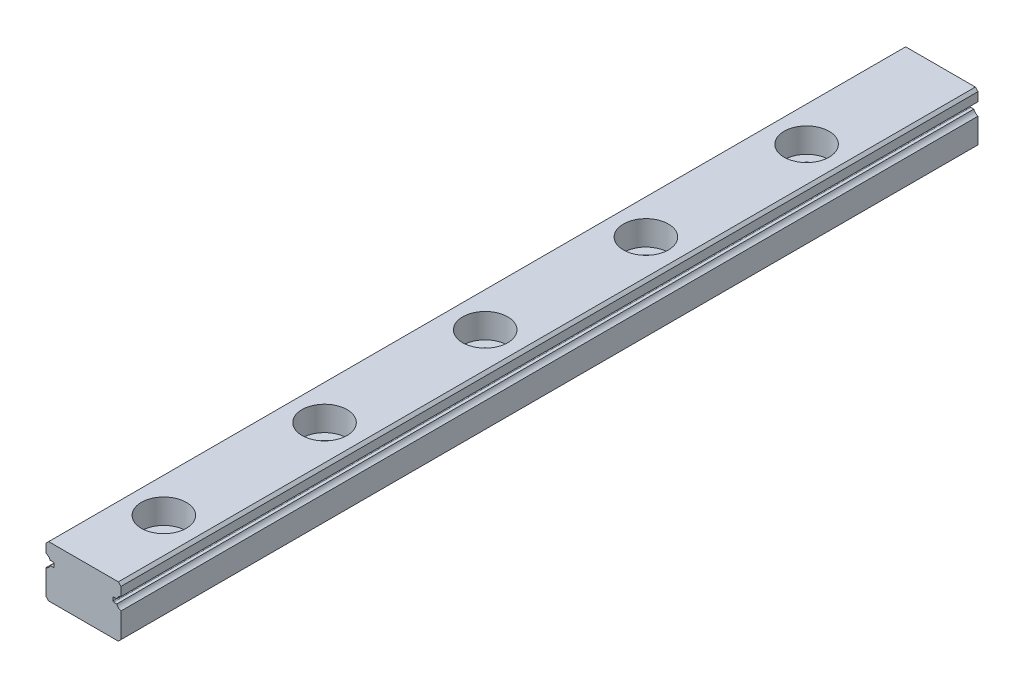
SolidWorks part; units mm, degrees
material "AISI 304"
ref_plane "前视基准面" through (0, 0, 0) normal (0, 0, 1) x (1, 0, 0)
ref_plane "上视基准面" through (0, 0, 0) normal (0, 1, 0) x (1, 0, 0)
ref_plane "右视基准面" through (0, 0, 0) normal (1, 0, 0) x (0, 0, -1)
other "Configuration Table"
sketch "草图2" plane through (0, 0, 0) normal (0, 0, 1) x (1, 0, 0)
  line L0 (3.2525, 4.8) -> (-3.2525, 4.8)
  line L1 (3.5, 4.5525) -> (3.2525, 4.8)
  line L2 (3.5, 3.7313) -> (3.5, 4.5525)
  line L3 (3.1055, 3.36) -> (2.8255, 3.36)
  line L4 (2.7555, 3.29) -> (2.7555, 3.01)
  line L5 (3.1055, 2.94) -> (2.8255, 2.94)
  line L6 (3.5, 0.2475) -> (3.5, 2.5687)
  line L7 (3.2525, 0) -> (3.5, 0.2475)
  line L8 (-3.2525, 0) -> (3.2525, 0)
  line L9 (-3.2525, 0) -> (-3.5, 0.2475)
  line L10 (-3.5, 0.2475) -> (-3.5, 2.5687)
  line L11 (-3.1055, 2.94) -> (-2.8255, 2.94)
  line L12 (-2.7555, 3.29) -> (-2.7555, 3.01)
  line L13 (-3.1055, 3.36) -> (-2.8255, 3.36)
  line L14 (-3.5, 3.7313) -> (-3.5, 4.5525)
  line L15 (-3.5, 4.5525) -> (-3.2525, 4.8)
  arc A0 (3.5, 3.7313) -> (3.1055, 3.36) centre (3.675, 3.15) ccw
  arc A1 (2.8255, 3.36) -> (2.7555, 3.29) centre (2.8255, 3.29) ccw
  arc A2 (2.7555, 3.01) -> (2.8255, 2.94) centre (2.8255, 3.01) ccw
  arc A3 (3.1055, 2.94) -> (3.5, 2.5687) centre (3.675, 3.15) ccw
  arc A4 (-3.5, 2.5687) -> (-3.1055, 2.94) centre (-3.675, 3.15) ccw
  arc A5 (-2.8255, 2.94) -> (-2.7555, 3.01) centre (-2.8255, 3.01) ccw
  arc A6 (-2.7555, 3.29) -> (-2.8255, 3.36) centre (-2.8255, 3.29) ccw
  arc A7 (-3.1055, 3.36) -> (-3.5, 3.7313) centre (-3.675, 3.15) ccw
  dimension "D1" = 0.607
  dimension "D2" = 0.07
  dimension "D3" = 0.147
  dimension "D4" = 0.497
  dimension "D5" = 6.008
  dimension "D6" = 6.7525
  dimension "D7" = 3.15
  dimension "D8" = 4.8
extrude "凸台-拉伸1" add sketch "草图2" against normal blind 80
sketch "草图3" plane through (0, 0, 0) normal (1, 0, 0) x (0, 0, -1)
  line L0 (5.4, 4.8) -> (5.4, 2.5)
  line L1 (5.4, 2.5) -> (6.3, 2.5)
  line L2 (6.3, 2.5) -> (6.3, 0)
  line L3 (5.4, 4.8) -> (7.5, 4.8)
  line L4 (7.5, 4.8) -> (7.5, 0)
  line L5 (7.5, 0) -> (6.3, 0)
  line L6 (80, 0) -> (0, 0) construction
  line L7 (0, 3.7313) -> (0, 4.5525) construction
  dimension "D1" = 1.2
  dimension "D2" = 2.1
  dimension "D3" = 2.5
  dimension "D4" = 4.8
  dimension "D5" = 7.5
revolve "切除-旋转1" cut sketch "草图3" angle 360 about L4
pattern_linear "阵列(线性)1" count 5 spacing 15 along (0, 0, -1) of "切除-旋转1"
equation "\"D\"= 7.5'端孔距[3,12]"
equation "\"L\" = 80'总长"
equation "\"D1@凸台-拉伸1\"=\"L\""
equation "\"H\"= 15'孔距（勿动）"
equation "\"D1@阵列(线性)1\"= int ( \"L\" / \"H\" )'孔数"
equation "\"D3@阵列(线性)1\"=\"H\""
equation "\"D5@草图3\"=\"D\""
